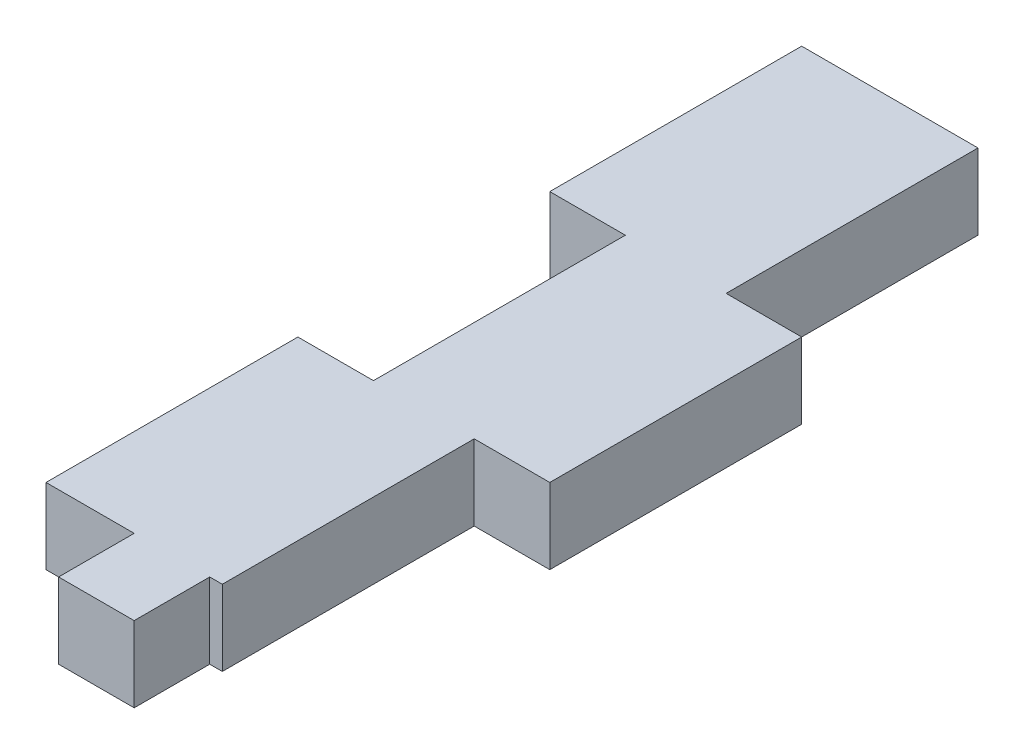
SolidWorks part; units mm, degrees
ref_plane "前视基准面" through (0, 0, 0) normal (0, 0, 1) x (1, 0, 0)
ref_plane "上视基准面" through (0, 0, 0) normal (0, 1, 0) x (1, 0, 0)
ref_plane "右视基准面" through (0, 0, 0) normal (1, 0, 0) x (0, 0, -1)
other "Configuration Table"
sketch "草图1" plane through (0, 0, 0) normal (0, 1, 0) x (1, 0, 0)
  line L1 (0, 0) -> (7, 0)
  line L2 (0, 0) -> (0, -30)
  line L3 (0, -30) -> (7, -30)
  line L4 (7, 0) -> (7, -30)
  line L5 (3.5, -30) -> (6.5, -30)
  line L6 (3.5, -30) -> (3.5, -33)
  line L7 (3.5, -33) -> (6.5, -33)
  line L8 (6.5, -30) -> (6.5, -33)
  line L9 (0, -10) -> (3, -10)
  line L10 (0, -10) -> (0, -20)
  line L11 (0, -20) -> (3, -20)
  line L12 (3, -10) -> (3, -20)
  line L17 (7, -10) -> (10, -10)
  line L18 (7, -10) -> (7, -20)
  line L19 (7, -20) -> (10, -20)
  line L20 (10, -10) -> (10, -20)
  dimension "D1" = 7
  dimension "D2" = 3
  dimension "D3" = 3
  dimension "D4" = 3.5
  dimension "D5" = 30
  dimension "D6" = 3
  dimension "D7" = 10
  dimension "D8" = 10
  dimension "D9" = 3
  dimension "D10" = 10
  dimension "D11" = 10
extrude "凸台-拉伸1" add sketch "草图1" along normal blind 3 contours L4 L1 L2 L3 | L8 L3 L6 L7 | L20 L17 L4 L19
